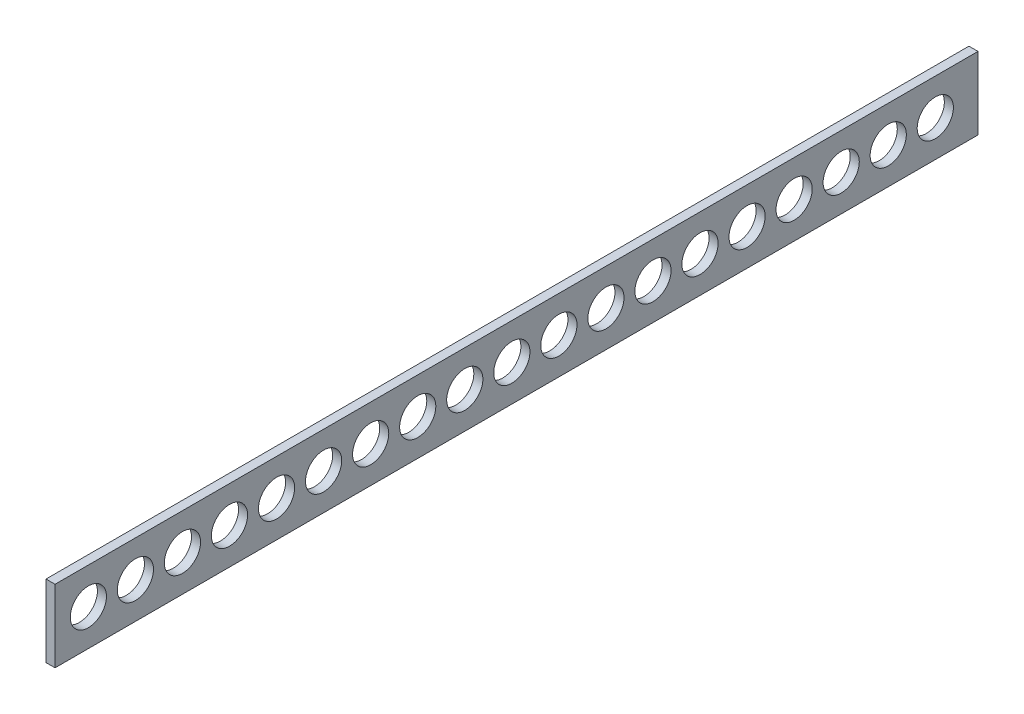
SolidWorks part; units mm, degrees
ref_plane "Front Plane" through (0, 0, 0) normal (0, 0, 1) x (1, 0, 0)
ref_plane "Top Plane" through (0, 0, 0) normal (0, 1, 0) x (1, 0, 0)
ref_plane "Right Plane" through (0, 0, 0) normal (1, 0, 0) x (0, 0, -1)
sketch "Sketch1" plane through (0, 0, 0) normal (1, 0, 0) x (0, 0, -1)
  line L0 (0, 25.4) -> (647.7, 25.4) construction
  line L1 (0, 0) -> (647.7, 0)
  line L2 (0, 0) -> (0, 50.8)
  line L3 (0, 50.8) -> (647.7, 50.8)
  line L4 (647.7, 0) -> (647.7, 50.8)
  circle A0 centre (23.3708, 25.4) radius 12.7
  circle A1 centre (56.3908, 25.4) radius 12.7
  circle A2 centre (89.4108, 25.4) radius 12.7
  circle A3 centre (122.4308, 25.4) radius 12.7
  circle A4 centre (155.4508, 25.4) radius 12.7
  circle A5 centre (188.4708, 25.4) radius 12.7
  circle A6 centre (221.4908, 25.4) radius 12.7
  circle A7 centre (254.5108, 25.4) radius 12.7
  circle A8 centre (287.5308, 25.4) radius 12.7
  circle A9 centre (320.5508, 25.4) radius 12.7
  circle A10 centre (353.5708, 25.4) radius 12.7
  circle A11 centre (386.5908, 25.4) radius 12.7
  circle A12 centre (419.6108, 25.4) radius 12.7
  circle A13 centre (452.6308, 25.4) radius 12.7
  circle A14 centre (485.6508, 25.4) radius 12.7
  circle A15 centre (518.6708, 25.4) radius 12.7
  circle A16 centre (551.6908, 25.4) radius 12.7
  circle A17 centre (584.7108, 25.4) radius 12.7
  circle A18 centre (617.7308, 25.4) radius 12.7
  dimension "D2" = 25.4
  dimension "D1" = 647.7
  dimension "D4" = 50.8
  dimension "D3" = 19
extrude "Boss-Extrude1" add sketch "Sketch1" along normal blind 6.35
